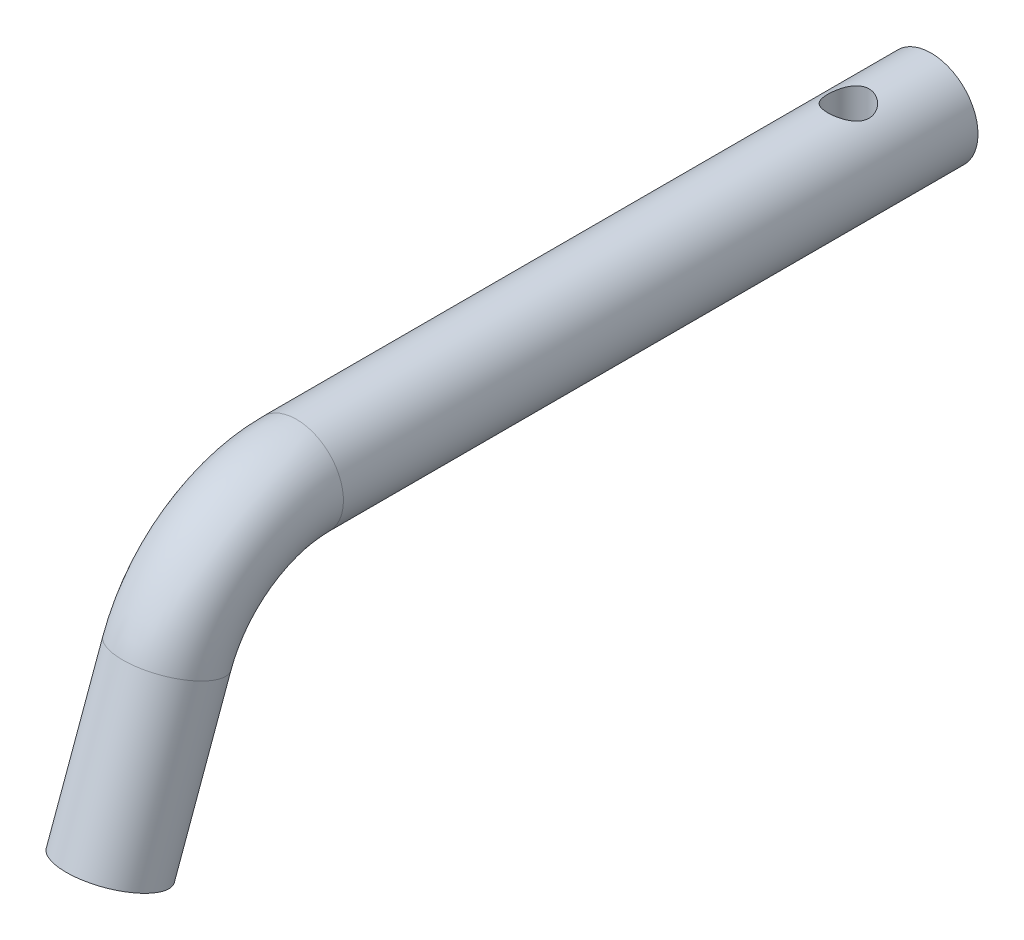
SolidWorks part; units mm, degrees
material "6061 Alloy"
ref_plane "Front Plane" through (0, 0, 0) normal (0, 0, 1) x (1, 0, 0)
ref_plane "Top Plane" through (0, 0, 0) normal (0, 1, 0) x (1, 0, 0)
ref_plane "Right Plane" through (0, 0, 0) normal (1, 0, 0) x (0, 0, -1)
sketch "Sketch1" plane through (0, 0, 0) normal (1, 0, 0) x (0, 0, -1)
  line L0 (0, 0) -> (-115, 0)
  line L1 (-138.4923, -16.4495) -> (-148.7529, -44.6403)
  arc A0 (-115, 0) -> (-138.4923, -16.4495) centre (-115, -25) ccw
  dimension "D2" = 25
  dimension "D1" = 115
  dimension "D3" = 30
  dimension "D4" = 110
sketch "Sketch2" plane through (0, 0, 0) normal (0, 0, 1) x (1, 0, 0)
  circle A0 centre (0, 0) radius 8.5
  dimension "D1" = 17
sweep "Sweep1" add profiles "Sketch2" path "Sketch1"
sketch "Sketch3" plane through (0, 0, 0) normal (0, 1, 0) x (1, 0, 0)
  line L0 (0, -15) -> (0, 0) construction
  circle A0 centre (0, -15) radius 3.75
  dimension "D1" = 7.5
  dimension "D2" = 15
extrude "Cut-Extrude1" cut sketch "Sketch3" against normal through all both and the other way through all
